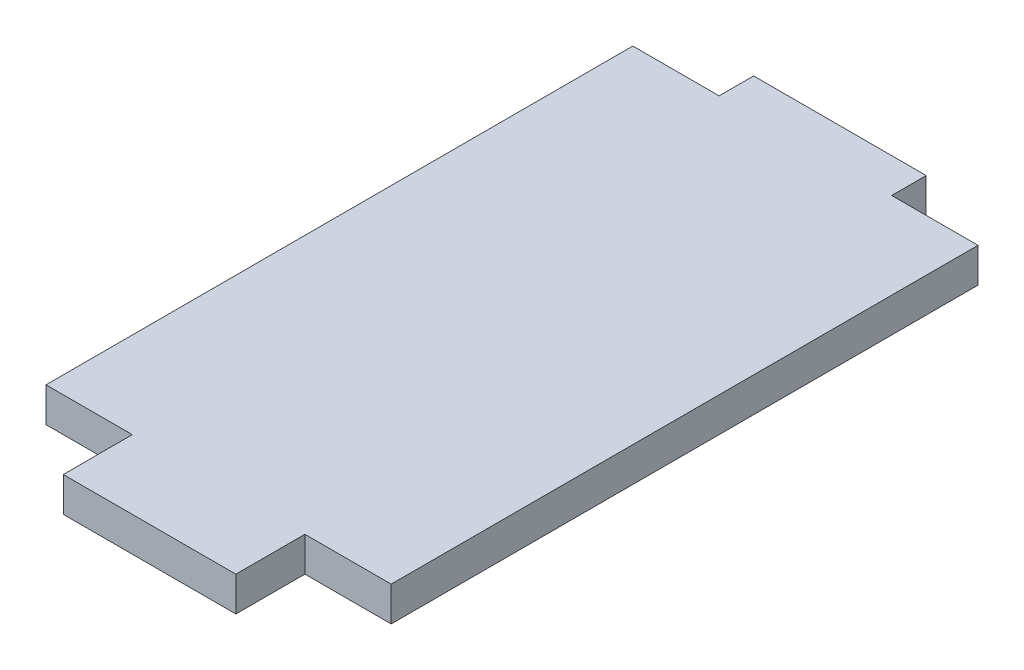
SolidWorks part; units mm, degrees
ref_plane "Front Plane" through (0, 0, 0) normal (0, 0, 1) x (1, 0, 0)
ref_plane "Top Plane" through (0, 0, 0) normal (0, 1, 0) x (1, 0, 0)
ref_plane "Right Plane" through (0, 0, 0) normal (1, 0, 0) x (0, 0, -1)
sketch "Sketch1" plane through (0, 0, 0) normal (0, 1, 0) x (1, 0, 0)
  line L0 (0, 25.5) -> (0, 0)
  line L1 (15, -25.5) -> (-15, -25.5)
  line L2 (15, -25.5) -> (15, 25.5)
  line L3 (15, 25.5) -> (-15, 25.5)
  line L4 (-15, -25.5) -> (-15, 25.5)
  line L5 (15, -25.5) -> (-15, 25.5) construction
  line L6 (15, 25.5) -> (-15, -25.5) construction
  line L15 (0, -25.5) -> (-7.5, -25.5)
  line L16 (0, -25.5) -> (0, -31.5)
  line L17 (0, -31.5) -> (-7.5, -31.5)
  line L18 (-7.5, -25.5) -> (-7.5, -31.5)
  line L19 (0, -25.5) -> (7.5, -25.5)
  line L20 (0, -25.5) -> (0, -31.5)
  line L21 (0, -31.5) -> (7.5, -31.5)
  line L22 (7.5, -25.5) -> (7.5, -31.5)
  line L23 (0, 0) -> (0, -25.5)
  line L24 (0, -12.75) -> (15, -12.75)
  line L25 (0, -12.75) -> (-15, -12.75)
  line L30 (6, -17.75) -> (9, -7.75) construction
  line L31 (6, -7.75) -> (9, -17.75) construction
  line L37 (-6, -17.75) -> (-9, -7.75) construction
  line L38 (-6, -7.75) -> (-9, -17.75) construction
  line L39 (7.5, 28.5) -> (-7.5, 28.5)
  line L40 (7.5, 28.5) -> (7.5, 25.5)
  line L41 (7.5, 25.5) -> (-7.5, 25.5)
  line L42 (-7.5, 28.5) -> (-7.5, 25.5)
  point P0 (0, 0)
  point P25 (7.5, -12.75)
  point P31 (-7.5, -12.75)
  dimension "D1" = 25.5
  dimension "D3" = 25.5
  dimension "D5" = 15
  dimension "D6" = 15
extrude "Boss-Extrude1" add sketch "Sketch1" along normal blind 3
